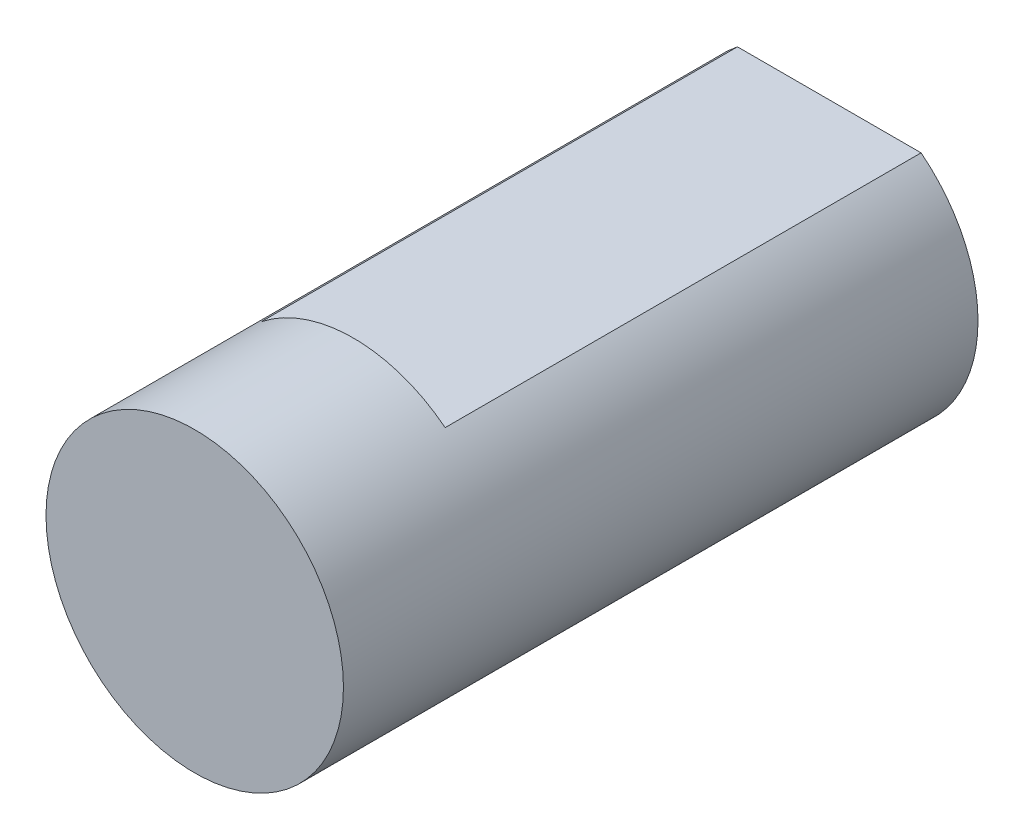
SolidWorks part; units mm, degrees
ref_plane "Front" through (0, 0, 0) normal (0, 0, 1) x (1, 0, 0)
ref_plane "Top" through (0, 0, 0) normal (0, 1, 0) x (1, 0, 0)
ref_plane "Right" through (0, 0, 0) normal (1, 0, 0) x (0, 0, -1)
sketch "Sketch1" plane through (0, 0, 0) normal (0, 0, 1) x (1, 0, 0)
  line L0 (-5.8805, 7.493) -> (5.8805, 7.493)
  line L1 (-5.8805, -7.493) -> (5.8805, -7.493)
  arc A0 (-5.8805, 7.493) -> (-5.8805, -7.493) centre (0, 0) ccw
  arc A1 (5.8805, -7.493) -> (5.8805, 7.493) centre (0, 0) ccw
  dimension "D1" = 19.05
  dimension "D2" = 14.986
extrude "Extrude1" add sketch "Sketch1" against normal blind 30.48
sketch "Sketch2" plane through (0, 0, 0) normal (0, 0, 1) x (1, 0, 0)
  circle A0 centre (0, 0) radius 9.525
  arc A1 (-5.8805, 7.493) -> (-5.8805, -7.493) centre (0, 0) ccw construction
extrude "Extrude2" add sketch "Sketch2" along normal blind 25.4
sketch "Sketch3" plane through (0, 0, -30.48) normal (0, 0, -1) x (-1, 0, 0)
  point P0 (0, 0)
sketch "Sketch4" plane through (0, 0, 25.4) normal (0, 0, 1) x (1, 0, 0)
  point P0 (0, 0)
hole_wizard "1/2-13 Tapped Hole1" positions "3DSketch1" profile "Sketch5" tap size "1/2-13" standard "Ansi Inch"
sketch3d "3DSketch1"
  point P0 (0, 0, -30.48)
sketch "Sketch5" plane through (0, 0, -30.48) normal (1, 0, 0) x (0, 1, 0)
  line L0 (0, 0) -> (0, 34.4793)
  line L1 (0, 34.4793) -> (5.3581, 31.2598)
  line L2 (5.3581, 31.2598) -> (5.3581, 0)
  line L5 (5.3581, 0) -> (0, 0)
  line L10 (0, 34.4793) -> (-5.3581, 31.2598) construction
  line L11 (0, -6.35) -> (0, 107.95) construction
  dimension "Tap Drill Dia." = 10.7163
  dimension "Tap Drill Depth" = 31.2598
  dimension "Drill Angle" = 118
cosmetic thread "Hole Thread1" parameters "D1"=25.4, "D2"=12.7
sketch "Sketch6" plane through (0, 0, 25.4) normal (0, 0, 1) x (1, 0, 0)
  circle A0 centre (0, 0) radius 9.525 construction
  circle A1 centre (0, 0) radius 9.525
extrude "Cut-Extrude1" cut sketch "Sketch6" against normal blind 15.24
